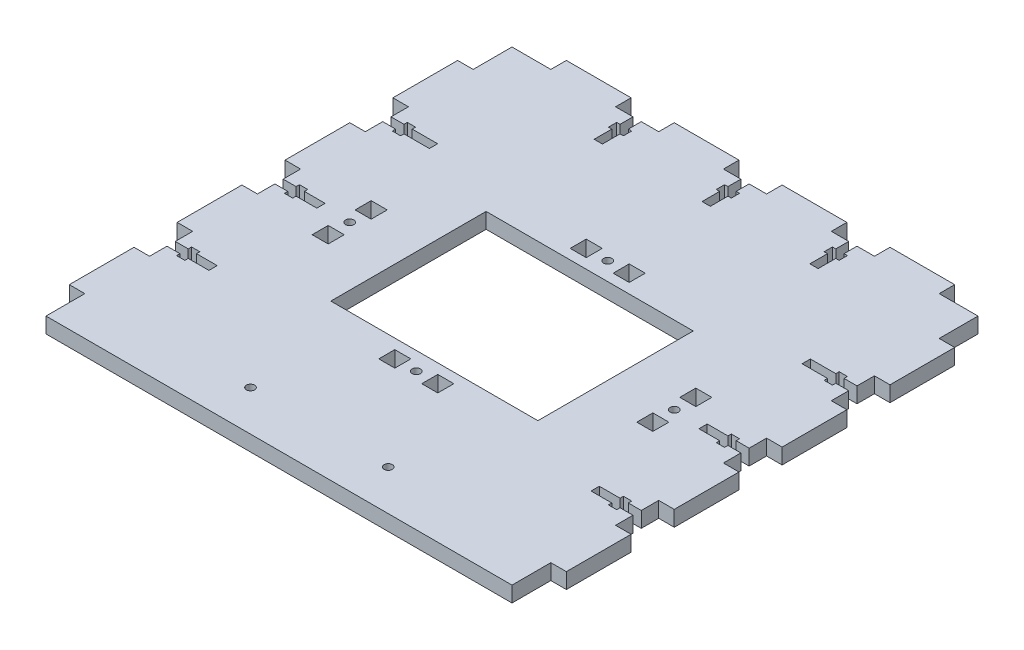
SolidWorks part; units mm, degrees
material "Oak"
ref_plane "Front Plane" through (0, 0, 0) normal (0, 0, 1) x (1, 0, 0)
ref_plane "Top Plane" through (0, 0, 0) normal (0, 1, 0) x (1, 0, 0)
ref_plane "Right Plane" through (0, 0, 0) normal (1, 0, 0) x (0, 0, -1)
sketch "Sketch1" plane through (0, 0, 0) normal (0, 1, 0) x (1, 0, 0)
  line L0 (0, -90) -> (0, 90) construction
  line L2 (90, 43.2667) -> (85, 43.2667)
  line L3 (90, 43.2667) -> (90, 40.0667)
  line L4 (90, 40.0667) -> (85, 40.0667)
  line L5 (72, 43.2667) -> (72, 40.0667)
  line L6 (81.8, 40.0667) -> (72, 40.0667)
  line L7 (81.8, 44.5667) -> (85, 44.5667)
  line L8 (81.8, 44.5667) -> (81.8, 43.2667)
  line L9 (81.8, 38.7667) -> (85, 38.7667)
  line L10 (85, 44.5667) -> (85, 43.2667)
  line L11 (81.8, 40.0667) -> (81.8, 38.7667)
  line L12 (81.8, 43.2667) -> (72, 43.2667)
  line L13 (85, 40.0667) -> (85, 38.7667)
  line L14 (90, 43.2667) -> (90, 50) construction
  line L15 (90, 40.0667) -> (90, 33.3333) construction
  line L16 (-85, 40.0667) -> (-85, 38.7667)
  line L17 (-81.8, 43.2667) -> (-72, 43.2667)
  line L18 (-81.8, 40.0667) -> (-81.8, 38.7667)
  line L19 (-85, 44.5667) -> (-85, 43.2667)
  line L20 (-81.8, 38.7667) -> (-85, 38.7667)
  line L21 (-81.8, 44.5667) -> (-81.8, 43.2667)
  line L22 (-81.8, 44.5667) -> (-85, 44.5667)
  line L23 (-81.8, 40.0667) -> (-72, 40.0667)
  line L24 (-72, 43.2667) -> (-72, 40.0667)
  line L25 (-90, 40.0667) -> (-85, 40.0667)
  line L26 (-90, 43.2667) -> (-90, 40.0667)
  line L27 (-90, 43.2667) -> (-85, 43.2667)
  line L28 (-65.8, -5.2) -> (-65.8, -11.4)
  line L29 (-40, -30) -> (40, -30)
  line L30 (-40, -30) -> (-40, 30)
  line L31 (-40, 30) -> (40, 30)
  line L32 (40, -30) -> (40, 30)
  line L33 (-40, -30) -> (40, 30) construction
  line L34 (-40, 30) -> (40, -30) construction
  line L35 (-65.8, 11.4) -> (-59.6, 11.4)
  line L36 (-65.8, 11.4) -> (-65.8, 5.2)
  line L37 (-65.8, 5.2) -> (-59.6, 5.2)
  line L38 (-59.6, 11.4) -> (-59.6, 5.2)
  line L39 (-65.8, -5.2) -> (-59.6, -5.2)
  line L40 (-59.6, -5.2) -> (-59.6, -11.4)
  line L41 (-65.8, -11.4) -> (-59.6, -11.4)
  line L42 (-62.7, 5.2) -> (-62.7, -5.2) construction
  line L43 (0, -3.3) -> (0, 3.3) construction
  line L44 (65.8, -5.2) -> (59.6, -5.2)
  line L45 (59.6, -5.2) -> (59.6, -11.4)
  line L46 (65.8, -11.4) -> (59.6, -11.4)
  line L47 (65.8, -5.2) -> (65.8, -11.4)
  line L48 (65.8, 5.2) -> (59.6, 5.2)
  line L49 (59.6, 11.4) -> (59.6, 5.2)
  line L50 (65.8, 11.4) -> (59.6, 11.4)
  line L51 (65.8, 11.4) -> (65.8, 5.2)
  line L52 (-11.4, 40.0667) -> (-5.2, 40.0667) construction
  line L53 (-11.4, 40.0667) -> (-11.4, 33.8667) construction
  line L54 (-11.4, 33.8667) -> (-5.2, 33.8667) construction
  line L55 (-5.2, 40.0667) -> (-5.2, 33.8667) construction
  line L56 (11.4, 33.8667) -> (5.2, 33.8667) construction
  line L57 (5.2, 40.0667) -> (5.2, 33.8667) construction
  line L58 (11.4, 40.0667) -> (5.2, 40.0667) construction
  line L59 (11.4, 40.0667) -> (11.4, 33.8667) construction
  line L60 (-11.4, -33.8667) -> (-5.2, -33.8667) construction
  line L61 (-11.4, -40.0667) -> (-11.4, -33.8667) construction
  line L62 (-11.4, -40.0667) -> (-5.2, -40.0667) construction
  line L63 (-5.2, -40.0667) -> (-5.2, -33.8667) construction
  line L64 (11.4, -40.0667) -> (11.4, -33.8667) construction
  line L65 (11.4, -40.0667) -> (5.2, -40.0667) construction
  line L66 (5.2, -40.0667) -> (5.2, -33.8667) construction
  line L67 (11.4, -33.8667) -> (5.2, -33.8667) construction
  line L68 (-11.4, 40.0667) -> (-5.2, 40.0667)
  line L69 (-11.4, 40.0667) -> (-11.4, 33.8667)
  line L70 (-11.4, 33.8667) -> (-5.2, 33.8667)
  line L71 (-5.2, 40.0667) -> (-5.2, 33.8667)
  line L72 (11.4, 33.8667) -> (5.2, 33.8667)
  line L73 (5.2, 40.0667) -> (5.2, 33.8667)
  line L74 (11.4, 40.0667) -> (5.2, 40.0667)
  line L75 (11.4, 40.0667) -> (11.4, 33.8667)
  line L76 (-11.4, -33.8667) -> (-5.2, -33.8667)
  line L77 (-11.4, -40.0667) -> (-11.4, -33.8667)
  line L78 (-11.4, -40.0667) -> (-5.2, -40.0667)
  line L79 (-5.2, -40.0667) -> (-5.2, -33.8667)
  line L80 (11.4, -40.0667) -> (11.4, -33.8667)
  line L81 (11.4, -40.0667) -> (5.2, -40.0667)
  line L82 (5.2, -40.0667) -> (5.2, -33.8667)
  line L83 (11.4, -33.8667) -> (5.2, -33.8667)
  circle A0 centre (-62.7, 0) radius 1.6
  circle A1 centre (62.7, 0) radius 1.6
  circle A2 centre (0, 36.9667) radius 1.6 construction
  circle A3 centre (0, -36.9667) radius 1.6 construction
  circle A4 centre (0, 36.9667) radius 1.6
  circle A5 centre (0, -36.9667) radius 1.6
  circle A6 centre (-26.6, -74.4) radius 1.6 construction
  circle A7 centre (26.6, -74.4) radius 1.6 construction
  circle A8 centre (-26.6, -74.4) radius 1.6
  circle A9 centre (26.6, -74.4) radius 1.6
  point P29 (0, 0)
  point P38 (-59.6, -8.3)
  point P43 (-59.6, 8.3)
  point P46 (-62.7, 0)
  point P47 (-73.8, 0)
  line B0 (90, 90) -> (75, 90)
  line B1 (75, 90) -> (75, 96)
  line B2 (75, 96) -> (50, 96)
  line B3 (50, 96) -> (50, 90)
  line B4 (50, 90) -> (43.2667, 90)
  line B5 (43.2667, 90) -> (43.2667, 85)
  line B6 (43.2667, 85) -> (44.5667, 85)
  line B7 (44.5667, 85) -> (44.5667, 81.8)
  line B8 (44.5667, 81.8) -> (43.2667, 81.8)
  line B9 (43.2667, 81.8) -> (43.2667, 75)
  line B10 (43.2667, 75) -> (40.0667, 75)
  line B11 (40.0667, 75) -> (40.0667, 81.8)
  line B12 (40.0667, 81.8) -> (38.7667, 81.8)
  line B13 (38.7667, 81.8) -> (38.7667, 85)
  line B14 (38.7667, 85) -> (40.0667, 85)
  line B15 (40.0667, 85) -> (40.0667, 90)
  line B16 (40.0667, 90) -> (33.3333, 90)
  line B17 (33.3333, 90) -> (33.3333, 96)
  line B18 (33.3333, 96) -> (8.3333, 96)
  line B19 (8.3333, 96) -> (8.3333, 90)
  line B20 (8.3333, 90) -> (1.6, 90)
  line B21 (1.6, 90) -> (1.6, 85)
  line B22 (1.6, 85) -> (2.9, 85)
  line B23 (2.9, 85) -> (2.9, 81.8)
  line B24 (2.9, 81.8) -> (1.6, 81.8)
  line B25 (1.6, 81.8) -> (1.6, 75)
  line B26 (1.6, 75) -> (-1.6, 75)
  line B27 (-1.6, 75) -> (-1.6, 81.8)
  line B28 (-1.6, 81.8) -> (-2.9, 81.8)
  line B29 (-2.9, 81.8) -> (-2.9, 85)
  line B30 (-2.9, 85) -> (-1.6, 85)
  line B31 (-1.6, 85) -> (-1.6, 90)
  line B32 (-1.6, 90) -> (-8.3333, 90)
  line B33 (-8.3333, 90) -> (-8.3333, 96)
  line B34 (-8.3333, 96) -> (-33.3333, 96)
  line B35 (-33.3333, 96) -> (-33.3333, 90)
  line B36 (-33.3333, 90) -> (-40.0667, 90)
  line B37 (-40.0667, 90) -> (-40.0667, 85)
  line B38 (-40.0667, 85) -> (-38.7667, 85)
  line B39 (-38.7667, 85) -> (-38.7667, 81.8)
  line B40 (-38.7667, 81.8) -> (-40.0667, 81.8)
  line B41 (-40.0667, 81.8) -> (-40.0667, 75)
  line B42 (-40.0667, 75) -> (-43.2667, 75)
  line B43 (-43.2667, 75) -> (-43.2667, 81.8)
  line B44 (-43.2667, 81.8) -> (-44.5667, 81.8)
  line B45 (-44.5667, 81.8) -> (-44.5667, 85)
  line B46 (-44.5667, 85) -> (-43.2667, 85)
  line B47 (-43.2667, 85) -> (-43.2667, 90)
  line B48 (-43.2667, 90) -> (-50, 90)
  line B49 (-50, 90) -> (-50, 96)
  line B50 (-50, 96) -> (-75, 96)
  line B51 (-75, 96) -> (-75, 90)
  line B52 (-75, 90) -> (-90, 90)
  line B53 (-90, 90) -> (-90, 75)
  line B54 (-90, 75) -> (-96, 75)
  line B55 (-96, 75) -> (-96, 50)
  line B56 (-96, 50) -> (-90, 50)
  line B57 (-90, 50) -> (-90, 33.3333)
  line B58 (-90, 33.3333) -> (-96, 33.3333)
  line B59 (-96, 33.3333) -> (-96, 8.3333)
  line B60 (-96, 8.3333) -> (-90, 8.3333)
  line B61 (-90, 8.3333) -> (-90, 1.6)
  line B62 (-90, 1.6) -> (-85, 1.6)
  line B63 (-85, 1.6) -> (-85, 2.9)
  line B64 (-85, 2.9) -> (-81.8, 2.9)
  line B65 (-81.8, 2.9) -> (-81.8, 1.6)
  line B66 (-81.8, 1.6) -> (-73.8, 1.6)
  line B67 (-73.8, 1.6) -> (-73.8, -1.6)
  line B68 (-73.8, -1.6) -> (-81.8, -1.6)
  line B69 (-81.8, -1.6) -> (-81.8, -2.9)
  line B70 (-81.8, -2.9) -> (-85, -2.9)
  line B71 (-85, -2.9) -> (-85, -1.6)
  line B72 (-85, -1.6) -> (-90, -1.6)
  line B73 (-90, -1.6) -> (-90, -8.3333)
  line B74 (-90, -8.3333) -> (-96, -8.3333)
  line B75 (-96, -8.3333) -> (-96, -33.3333)
  line B76 (-96, -33.3333) -> (-90, -33.3333)
  line B77 (-90, -33.3333) -> (-90, -40.0667)
  line B78 (-90, -40.0667) -> (-85, -40.0667)
  line B79 (-85, -40.0667) -> (-85, -38.7667)
  line B80 (-85, -38.7667) -> (-81.8, -38.7667)
  line B81 (-81.8, -38.7667) -> (-81.8, -40.0667)
  line B82 (-81.8, -40.0667) -> (-73.8, -40.0667)
  line B83 (-73.8, -40.0667) -> (-73.8, -43.2667)
  line B84 (-73.8, -43.2667) -> (-81.8, -43.2667)
  line B85 (-81.8, -43.2667) -> (-81.8, -44.5667)
  line B86 (-81.8, -44.5667) -> (-85, -44.5667)
  line B87 (-85, -44.5667) -> (-85, -43.2667)
  line B88 (-85, -43.2667) -> (-90, -43.2667)
  line B89 (-90, -43.2667) -> (-90, -50)
  line B90 (-90, -50) -> (-96, -50)
  line B91 (-96, -50) -> (-96, -75)
  line B92 (-96, -75) -> (-90, -75)
  line B93 (-90, -75) -> (-90, -90)
  line B94 (-90, -90) -> (90, -90)
  line B95 (90, -90) -> (90, -75)
  line B96 (90, -75) -> (96, -75)
  line B97 (96, -75) -> (96, -50)
  line B98 (96, -50) -> (90, -50)
  line B99 (90, -50) -> (90, -43.2667)
  line B100 (90, -43.2667) -> (85, -43.2667)
  line B101 (85, -43.2667) -> (85, -44.5667)
  line B102 (85, -44.5667) -> (81.8, -44.5667)
  line B103 (81.8, -44.5667) -> (81.8, -43.2667)
  line B104 (81.8, -43.2667) -> (73.8, -43.2667)
  line B105 (73.8, -43.2667) -> (73.8, -40.0667)
  line B106 (73.8, -40.0667) -> (81.8, -40.0667)
  line B107 (81.8, -40.0667) -> (81.8, -38.7667)
  line B108 (81.8, -38.7667) -> (85, -38.7667)
  line B109 (85, -38.7667) -> (85, -40.0667)
  line B110 (85, -40.0667) -> (90, -40.0667)
  line B111 (90, -40.0667) -> (90, -33.3333)
  line B112 (90, -33.3333) -> (96, -33.3333)
  line B113 (96, -33.3333) -> (96, -8.3333)
  line B114 (96, -8.3333) -> (90, -8.3333)
  line B115 (90, -8.3333) -> (90, -1.6)
  line B116 (90, -1.6) -> (85, -1.6)
  line B117 (85, -1.6) -> (85, -2.9)
  line B118 (85, -2.9) -> (81.8, -2.9)
  line B119 (81.8, -2.9) -> (81.8, -1.6)
  line B120 (81.8, -1.6) -> (73.8, -1.6)
  line B121 (73.8, -1.6) -> (73.8, 1.6)
  line B122 (73.8, 1.6) -> (81.8, 1.6)
  line B123 (81.8, 1.6) -> (81.8, 2.9)
  line B124 (81.8, 2.9) -> (85, 2.9)
  line B125 (85, 2.9) -> (85, 1.6)
  line B126 (85, 1.6) -> (90, 1.6)
  line B127 (90, 1.6) -> (90, 8.3333)
  line B128 (90, 8.3333) -> (96, 8.3333)
  line B129 (96, 8.3333) -> (96, 33.3333)
  line B130 (96, 33.3333) -> (90, 33.3333)
  line B131 (90, 33.3333) -> (90, 50)
  line B132 (90, 50) -> (96, 50)
  line B133 (96, 50) -> (96, 75)
  line B134 (96, 75) -> (90, 75)
  line B135 (90, 75) -> (90, 90)
  dimension "D12" = 3.2
  dimension "D1" = 3.2
  dimension "D2" = 5.8
  dimension "D3" = 3.2
  dimension "D4" = 18
  dimension "D5" = 5
  dimension "D6" = 60
  dimension "D7" = 80
  dimension "D8" = 6.2
  dimension "D9" = 6.2
  dimension "D11" = 16.6
  dimension "D13" = 8
  dimension "D10" = 2
sketch_block_instance "MainBody-1"
sketch_block "MainBody"
extrude "Boss-Extrude1" add sketch "Sketch1" along normal blind 6 contours B134 B135 B0 B1 B2 B3 B4 B5 B6 B7 B8 B9 B10 B11 B12 B13 B14 B15 B16 B17 B18 B19 B20 B21 B22 B23 B24 B25 B26 B27 B28 B29 B30 B31 B32 B33 B34 B35 B36 B37 B38 B39 B40 B41 B42 B43 B44 B45 B46 B47 B48
